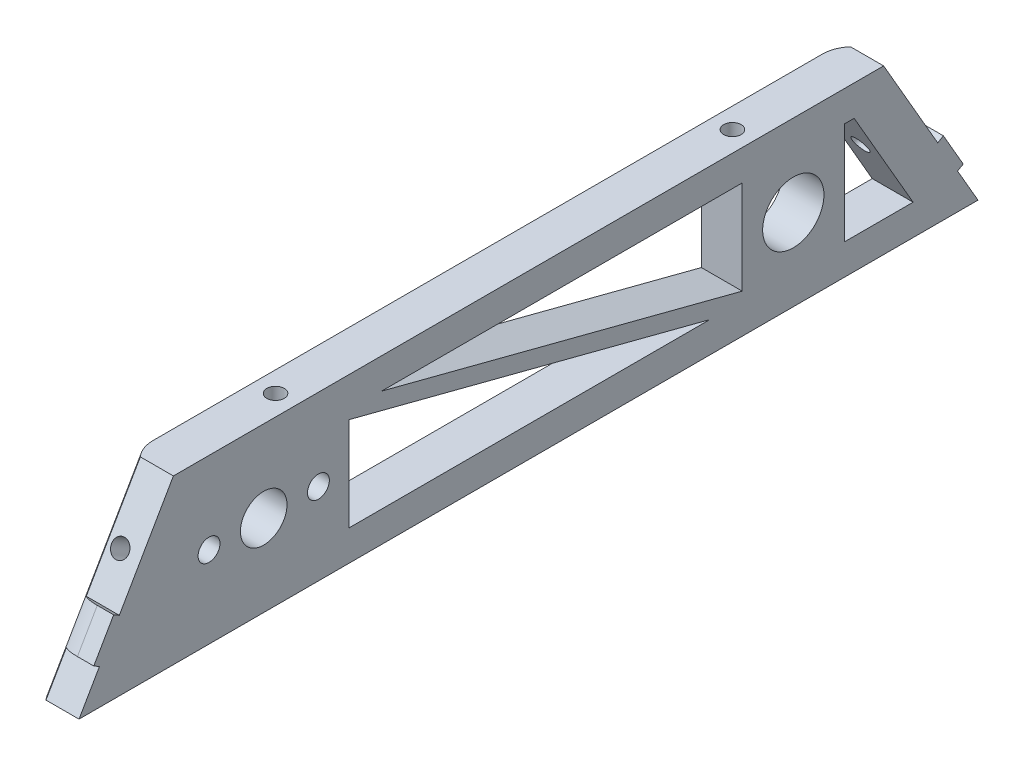
SolidWorks part; units mm, degrees
material "6061-T6 (SS)"
ref_plane "Front Plane" through (0, 0, 0) normal (0, 0, 1) x (1, 0, 0)
ref_plane "Top Plane" through (0, 0, 0) normal (0, 1, 0) x (1, 0, 0)
ref_plane "Right Plane" through (0, 0, 0) normal (1, 0, 0) x (0, 0, -1)
sketch "Sketch1" plane through (0, 0, 0) normal (1, 0, 0) x (0, 0, -1)
  line L0 (0, 0) -> (-14.6647, 25.4)
  line L1 (0, 0) -> (-139.7, 0)
  line L3 (-14.6647, 25.4) -> (-125.0353, 25.4)
  line L5 (-139.7, 0) -> (-125.0353, 25.4)
  circle A0 centre (-110.998, 12.7) radius 3.6195
  circle A1 centre (-28.702, 12.7) radius 4.7625
  circle A2 centre (-102.498, 12.7) radius 1.7
  circle A3 centre (-119.498, 12.7) radius 1.7
  dimension "D3" = 7.239
  dimension "D5" = 9.525
  dimension "D9" = 3.4
  dimension "D2" = 25.4
  dimension "D4" = 12.7
  dimension "D6" = 139.7
  dimension "D7" = 28.702
  dimension "D8" = 12.7
  dimension "D10" = 8.5
  dimension "D11" = 8.5
  dimension "D13" = 60
  dimension "D14" = 60
  dimension "D15" = 28.702
extrude "Boss-Extrude1" add sketch "Sketch1" along normal blind 6.35
hole_wizard "Tap Drill for #6-32 Tap4" positions "Sketch7" profile "Sketch6" hole size "#6-32" standard "ANSI Inch"
sketch "Sketch7" plane through (0, 25.4, 0) normal (0, 1, 0) x (1, 0, 0)
  line L2 (0, -14.6647) -> (0, -125.0353) construction
  line L4 (6.35, -14.6647) -> (6.35, -125.0353) construction
  line L7 (6.35, -14.6647) -> (0, -14.6647) construction
  line L8 (6.35, -125.0353) -> (0, -125.0353) construction
  point P0 (3.175, -105.9853)
  point P2 (3.175, -34.9847)
  point P16 (3.175, -34.9847)
  point P18 (3.175, -105.9853)
  point P22 (3.175, -105.9853)
  dimension "D1" = 19.05
  dimension "D2" = 20.32
  dimension "D3" = 3.175
  dimension "D4" = 3.175
sketch "Sketch6" plane through (3.175, 25.4, 105.9853) normal (1, 0, 0) x (0, 0, 1)
  line L0 (0, 0) -> (0, 10.9727)
  line L1 (0, 10.9727) -> (1.3525, 10.16)
  line L2 (1.3525, 10.16) -> (1.3525, 0)
  line L5 (1.3525, 0) -> (0, 0)
  line L10 (0, 10.9727) -> (-1.3526, 10.16) construction
  line L11 (0, -6.35) -> (0, 107.95) construction
  dimension "Hole Dia." = 2.7051
  dimension "Hole Depth" = 10.16
  dimension "Drill Angle" = 118
hole_wizard "Tap Drill for #6-32 Tap3" positions "Sketch9" profile "Sketch8" hole size "#6-32" standard "ANSI Inch"
sketch "Sketch9" plane through (0, 0, 0) normal (0, -1, 0) x (-1, 0, 0)
  line L1 (0, -139.7) -> (0, 0) construction
  line L3 (-6.35, 0) -> (0, 0) construction
  line L4 (-6.35, -139.7) -> (0, -139.7) construction
  point P0 (-3.175, -105.41)
  point P2 (-3.175, -22.86)
  dimension "D1" = 22.86
  dimension "D2" = 3.175
  dimension "D3" = 34.29
  dimension "D4" = 3.175
sketch "Sketch8" plane through (3.175, 0, 105.41) normal (1, 0, 0) x (0, 0, -1)
  line L0 (0, 0) -> (0, 10.9727)
  line L1 (0, 10.9727) -> (1.3525, 10.16)
  line L2 (1.3525, 10.16) -> (1.3525, 0)
  line L5 (1.3525, 0) -> (0, 0)
  line L10 (0, 10.9727) -> (-1.3526, 10.16) construction
  line L11 (0, -6.35) -> (0, 107.95) construction
  dimension "Hole Dia." = 2.7051
  dimension "Hole Depth" = 10.16
  dimension "Drill Angle" = 118
sketch "Sketch11" plane through (0, 60.4919, 104.775) normal (0, 0.5, 0.866) x (1, 0, 0)
  line L0 (0, -40.5206) -> (0, -69.85) construction
  line L1 (0, -57.3278) -> (6.35, -57.3278)
  line L2 (0, -57.3278) -> (0, -63.5)
  line L3 (0, -63.5) -> (6.35, -63.5)
  line L4 (6.35, -57.3278) -> (6.35, -63.5)
  line L5 (6.35, -40.5206) -> (6.35, -69.85) construction
  line L6 (6.35, -69.85) -> (0, -69.85) construction
  dimension "D1" = 6.1722
  dimension "D2" = 6.35
extrude "Boss-Extrude2" add sketch "Sketch11" along normal blind 1.016
sketch "Sketch12" plane through (0, 0, 0) normal (0, 0.5, -0.866) x (-1, 0, 0)
  line L0 (-6.35, 0) -> (-6.35, 29.3294) construction
  line L1 (-6.35, 12.5222) -> (0, 12.5222)
  line L2 (-6.35, 12.5222) -> (-6.35, 6.35)
  line L3 (-6.35, 6.35) -> (0, 6.35)
  line L4 (0, 12.5222) -> (0, 6.35)
  line L5 (0, 0) -> (0, 29.3294) construction
  line L6 (-6.35, 0) -> (0, 0) construction
  dimension "D1" = 6.1722
  dimension "D2" = 6.35
extrude "Boss-Extrude3" add sketch "Sketch12" along normal blind 1.016
hole_wizard "Tap Drill for #6-32 Tap1" positions "Sketch14" profile "Sketch13" hole size "#6-32" standard "ANSI Inch"
sketch "Sketch14" plane through (0, 60.4919, 104.775) normal (0, 0.5, 0.866) x (1, 0, 0)
  line L0 (6.35, -40.5206) -> (6.35, -57.3278) construction
  line L1 (6.35, -40.5206) -> (0, -40.5206) construction
  point P0 (3.175, -50.6806)
  dimension "D1" = 3.175
  dimension "D2" = 10.16
sketch "Sketch13" plane through (3.175, 16.6012, 130.1153) normal (1, 0, 0) x (0, -0.866, 0.5)
  line L0 (0, 0) -> (0, 8.4327)
  line L1 (0, 8.4327) -> (1.3525, 7.62)
  line L2 (1.3525, 7.62) -> (1.3525, 0)
  line L5 (1.3525, 0) -> (0, 0)
  line L10 (0, 8.4327) -> (-1.3526, 7.62) construction
  line L11 (0, -6.35) -> (0, 107.95) construction
  dimension "Hole Dia." = 2.7051
  dimension "Hole Depth" = 7.62
  dimension "Drill Angle" = 118
hole_wizard "Tap Drill for #6-32 Tap2" positions "Sketch16" profile "Sketch15" hole size "#6-32" standard "ANSI Inch"
sketch "Sketch16" plane through (0, 0, 0) normal (0, 0.5, -0.866) x (-1, 0, 0)
  line L0 (0, 12.5222) -> (0, 29.3294) construction
  line L1 (-6.35, 29.3294) -> (0, 29.3294) construction
  point P0 (-3.175, 19.1694)
  dimension "D1" = 3.175
  dimension "D2" = 10.16
sketch "Sketch15" plane through (3.175, 16.6012, 9.5847) normal (1, 0, 0) x (0, 0.866, 0.5)
  line L0 (0, 0) -> (0, 8.4327)
  line L1 (0, 8.4327) -> (1.3525, 7.62)
  line L2 (1.3525, 7.62) -> (1.3525, 0)
  line L5 (1.3525, 0) -> (0, 0)
  line L10 (0, 8.4327) -> (-1.3525, 7.62) construction
  line L11 (0, -6.35) -> (0, 107.95) construction
  dimension "Hole Dia." = 2.7051
  dimension "Hole Depth" = 7.62
  dimension "Drill Angle" = 118
sketch "Sketch19" plane through (0, 0, 0) normal (-1, 0, 0) x (0, 0, 1)
  line L0 (14.6647, 25.4) -> (125.0353, 25.4) construction
  line L1 (36.6395, 20.6375) -> (97.7355, 20.6375)
  line L2 (36.6395, 20.6375) -> (36.6395, 4.7625)
  line L3 (36.6395, 4.7625) -> (97.7355, 4.7625)
  line L4 (97.7355, 20.6375) -> (97.7355, 4.7625)
  line L5 (139.7, 0) -> (0, 0) construction
  line L6 (36.6395, 4.7625) -> (97.7355, 20.6375) construction
  line L7 (41.6895, 4.7625) -> (97.7355, 19.3253)
  line L8 (36.6395, 6.0747) -> (92.6855, 20.6375)
  line L9 (36.3201, 5.9917) -> (97.4161, 21.8667) construction
  line L10 (36.9589, 3.5333) -> (98.0549, 19.4083) construction
  line L11 (10.082, 4.7625) -> (19.2474, 20.6375)
  line L12 (20.7645, 20.6375) -> (20.7645, 4.7625)
  line L13 (20.7645, 4.7625) -> (10.082, 4.7625)
  line L14 (6.2611, 10.8445) -> (14.6647, 25.4) construction
  line L15 (20.7645, 20.6375) -> (19.2474, 20.6375)
  circle A0 centre (28.702, 12.7) radius 4.7625 construction
  circle A1 centre (102.498, 12.7) radius 1.7 construction
  dimension "D1" = 4.7625
  dimension "D2" = 4.7625
  dimension "D3" = 7.9375
  dimension "D4" = 4.7625
  dimension "D7" = 6.35
  dimension "D8" = 7.9375
  dimension "D9" = 4.7625
  dimension "D5" = 1.27
  dimension "D6" = 1.27
extrude "Cut-Extrude1" cut sketch "Sketch19" against normal through all contours L2 L8 L1 | L7 L3 L4 | L12 L15 L11 L13
fillet "Fillet1" radius 3.81 2 edges at (0, 8.6799, 135.8618) (0, 8.6799, 3.8382)
equation "\"D8@Sketch1\"=\"D4@Sketch1\""
equation "\"D11@Sketch1\"=\"D10@Sketch1\""
